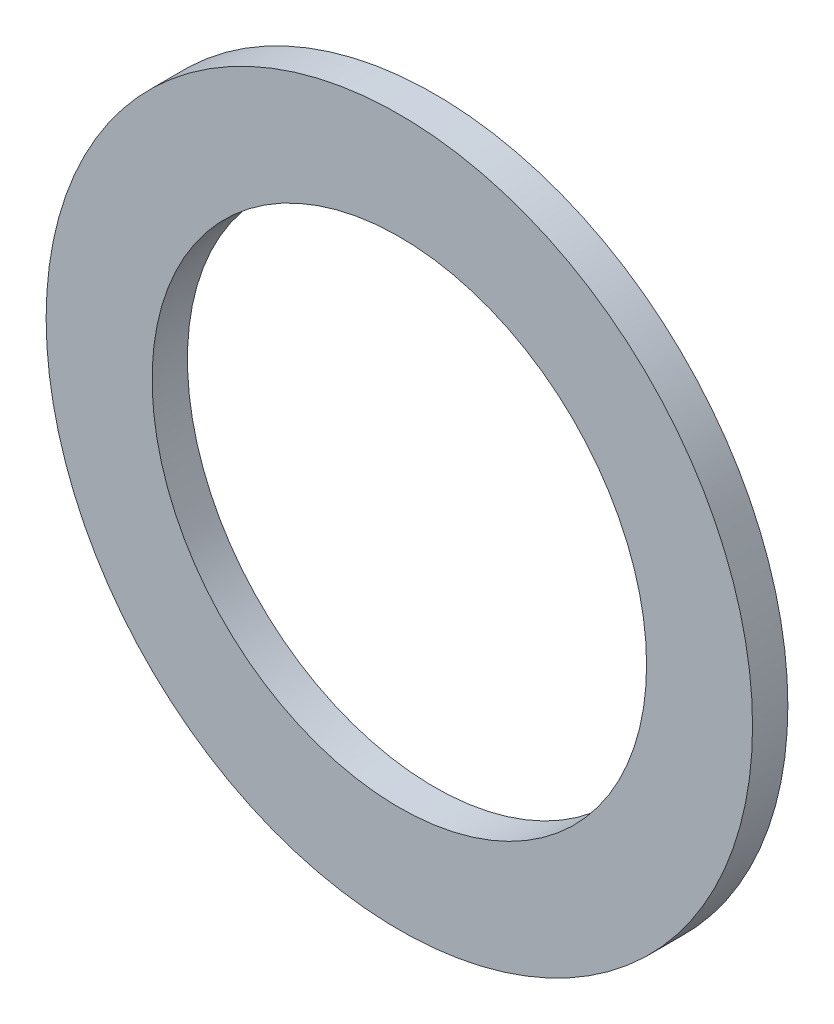
SolidWorks part; units mm, degrees
material "钢"
ref_plane "前视基准面" through (0, 0, 0) normal (0, 0, 1) x (1, 0, 0)
ref_plane "上视基准面" through (0, 0, 0) normal (0, 1, 0) x (1, 0, 0)
ref_plane "右视基准面" through (0, 0, 0) normal (1, 0, 0) x (0, 0, -1)
sketch "草图1" plane through (0, 0, 0) normal (0, 0, 1) x (1, 0, 0)
  circle A0 centre (0, 0) radius 5
  circle A1 centre (0, 0) radius 3.5
  dimension "d2" = 10
  dimension "d1" = 7
extrude "拉伸1" add sketch "草图1" along normal blind 0.5
